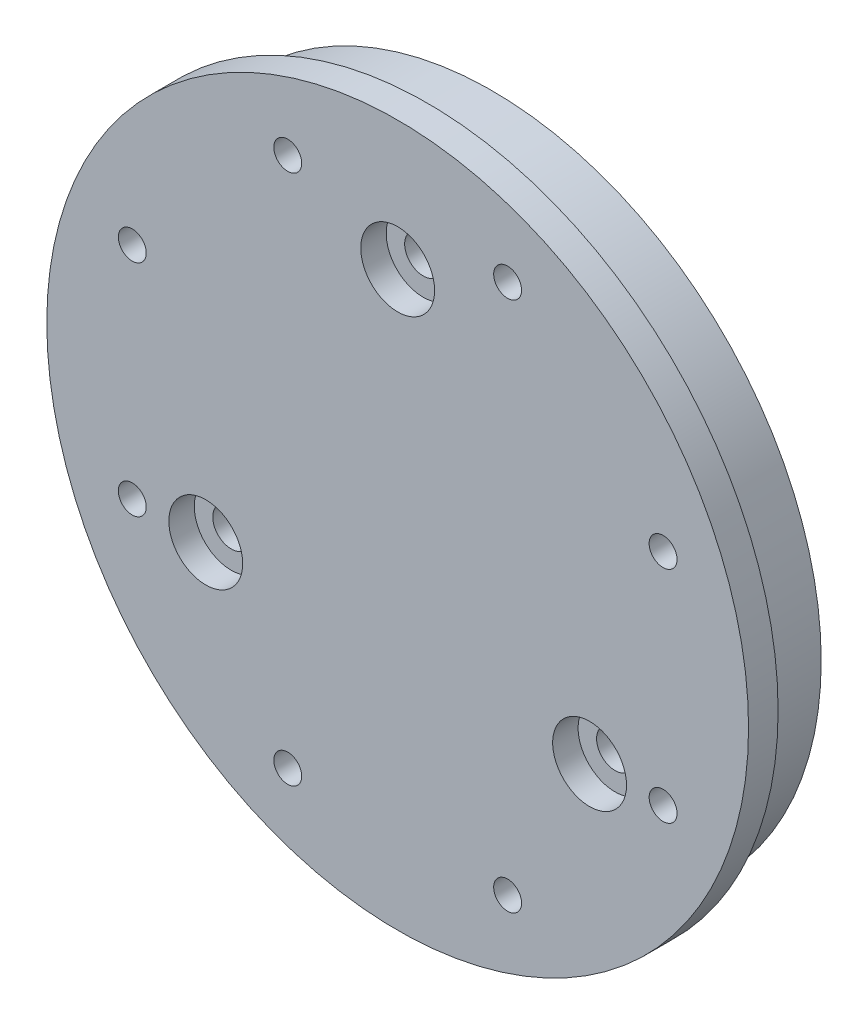
SolidWorks part; units mm, degrees
material "7075-O (SS)"
ref_plane "Front" through (0, 0, 0) normal (0, 0, 1) x (1, 0, 0)
ref_plane "Top" through (0, 0, 0) normal (0, 1, 0) x (1, 0, 0)
ref_plane "Right" through (0, 0, 0) normal (1, 0, 0) x (0, 0, -1)
sketch "Croquis1" plane through (0, 0, 0) normal (0, 0, 1) x (1, 0, 0)
  circle A0 centre (0, 0) radius 40.1
  dimension "D1" = 80.2
extrude "Saliente-Extruir1" add sketch "Croquis1" along normal mid plane 7.9
sketch "Croquis2" plane through (0, 0, 3.95) normal (0, 0, 1) x (1, 0, 0)
  circle A0 centre (0, 0) radius 42.75
  dimension "D1" = 85.5
extrude "Saliente-Extruir2" add sketch "Croquis2" along normal blind 3.6
hole_wizard "Refrentado para tornillo con cabeza troncocónica de M41" positions "Croquis3" profile "Croquis5" counterbore size "M4" standard "Ansi Metric" end condition up to next
sketch "Croquis3" plane through (0, 0, 7.55) normal (0, 0, 1) x (1, 0, 0)
  line L0 (0, -6.325) -> (0, 6.325) construction
  point P0 (0, 27)
  point P10 (23.3827, -13.5)
  point P11 (-23.3827, -13.5)
  dimension "D1" = 27
  dimension "D2" = 3
sketch "Croquis5" plane through (0, 27, 7.55) normal (1, 0, 0) x (0, -1, 0)
  line L0 (0, 0) -> (0, 11.5)
  line L1 (0, 11.5) -> (2.25, 11.5)
  line L3 (2.25, 11.5) -> (2.25, 3.1)
  line L4 (2.25, 3.1) -> (4.5, 3.1)
  line L5 (4.5, 3.1) -> (4.5, 0)
  line L7 (4.5, 0) -> (0, 0)
  line L11 (0, -6.35) -> (0, 107.95) construction
  dimension "Diámetro de taladro hasta el siguiente" = 4.5
  dimension "Profundidad de taladro hasta el siguiente" = 11.5
  dimension "Diámetro de refrentado" = 9
  dimension "Profundidad de refrentado" = 3.1
sketch "Croquis6" plane through (0, 0, -3.95) normal (0, 0, -1) x (-1, 0, 0)
  line L0 (0, 20) -> (0, 0) construction
  line L1 (0, 6.325) -> (0, -6.325) construction
  line L2 (0, 0) -> (17.3205, -10) construction
  line L3 (0, 0) -> (-17.3205, -10) construction
  line L4 (5, 20) -> (5, 2.8868)
  line L5 (0, -5.7735) -> (-14.8205, -14.3301)
  line L6 (5, 2.8868) -> (19.8205, -5.6699)
  line L7 (-5, 20) -> (-5, 2.8868)
  line L8 (-5, 2.8868) -> (-19.8205, -5.6699)
  line L9 (0, -5.7735) -> (14.8205, -14.3301)
  line L10 (-19.8205, -5.6699) -> (-14.8205, -14.3301)
  line L11 (14.8205, -14.3301) -> (19.8205, -5.6699)
  line L12 (5, 20) -> (-5, 20)
  line L13 (-2.5, 4.3301) -> (-19.8205, -5.6699) construction
  line L14 (-5, 20) -> (-5, 0) construction
  line L15 (-2.5, -4.3301) -> (14.8205, -14.3301) construction
  line L16 (2.5, -4.3301) -> (-14.8205, -14.3301) construction
  line L17 (5, 20) -> (5, 0) construction
  line L18 (2.5, 4.3301) -> (19.8205, -5.6699) construction
  dimension "D1" = 20
  dimension "D2" = 120
  dimension "D3" = 120
  dimension "D4" = 5
  dimension "D5" = 5
extrude "Saliente-Extruir3" add sketch "Croquis6" along normal blind 3.6
hole_wizard "Taladro de margen para M32" positions "Croquis7" profile "Croquis9" hole size "M3" standard "Ansi Metric" end condition up to next
sketch "Croquis7" plane through (0, 0, 7.55) normal (0, 0, 1) x (1, 0, 0)
  line L0 (13.3939, 32.3358) -> (0, 0) construction
  line L3 (0, -6.325) -> (0, 6.325) construction
  line L4 (0, 0) -> (-13.3939, -32.3358) construction
  point P0 (13.3939, 32.3358)
  point P17 (32.3358, 13.3939)
  point P18 (32.3358, -13.3939)
  point P19 (13.3939, -32.3358)
  point P20 (-13.3939, -32.3358)
  point P21 (-32.3358, -13.3939)
  point P22 (-32.3358, 13.3939)
  point P23 (-13.3939, 32.3358)
  point P31 (0, 0)
  dimension "D1" = 35
  dimension "D2" = 22.5
  dimension "D3" = 8
sketch "Croquis9" plane through (13.3939, 32.3358, 7.55) normal (1, 0, 0) x (0, -1, 0)
  line L0 (0, 0) -> (0, 11.5)
  line L1 (0, 11.5) -> (1.7, 11.5)
  line L2 (1.7, 11.5) -> (1.7, 0)
  line L5 (1.7, 0) -> (0, 0)
  line L11 (0, -6.35) -> (0, 107.95) construction
  dimension "Diámetro de taladro hasta el siguiente" = 3.4
  dimension "Profundidad de taladro hasta el siguiente" = 11.5
